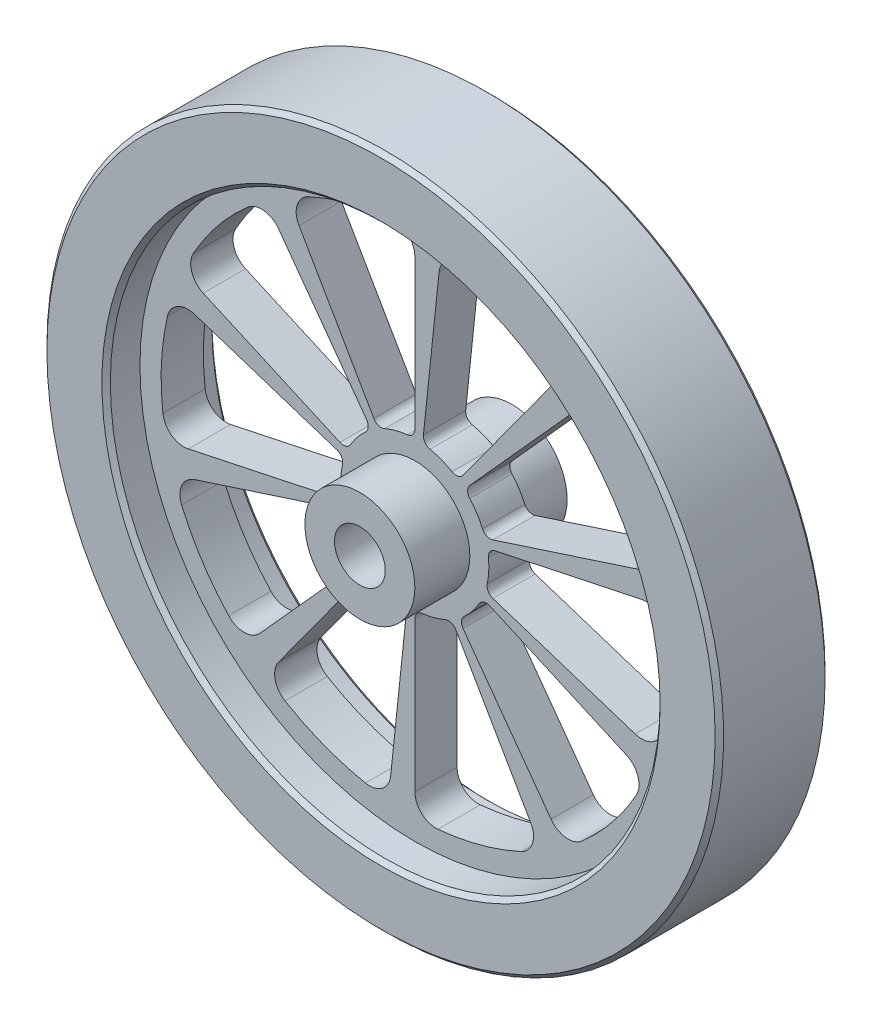
SolidWorks part; units mm, degrees
ref_plane "Front Plane" through (0, 0, 0) normal (0, 0, 1) x (1, 0, 0)
ref_plane "Top Plane" through (0, 0, 0) normal (0, 1, 0) x (1, 0, 0)
ref_plane "Right Plane" through (0, 0, 0) normal (1, 0, 0) x (0, 0, -1)
sketch "Sketch1" plane through (0, 0, 0) normal (0, 0, 1) x (1, 0, 0)
  circle A0 centre (0, 0) radius 80
  circle A1 centre (0, 0) radius 6
  dimension "D1" = 160
  dimension "D2" = 12
extrude "Boss-Extrude1" add sketch "Sketch1" along normal mid plane 26
sketch "Sketch2" plane through (0, 0, 13) normal (0, 0, 1) x (1, 0, 0)
  circle A0 centre (0, 0) radius 65
  dimension "D1" = 130
extrude "Cut-Extrude1" cut sketch "Sketch2" against normal blind 8
mirror "Mirror1" about plane through (0, 0, 0) normal (0, 0, 1) of "Cut-Extrude1"
sketch "Sketch3" plane through (0, 0, 0) normal (0, 0, 1) x (1, 0, 0)
  circle A0 centre (0, 0) radius 6 construction
  circle A1 centre (0, 0) radius 6
  circle A2 centre (0, 0) radius 13
  dimension "D1" = 26
extrude "Boss-Extrude2" add sketch "Sketch3" along normal mid plane 36
chamfer "Chamfer1" distance 1 angle 45 2 edges at (80, 0, -13) (80, 0, 13)
sketch "Sketch4" plane through (0, 0, 5) normal (0, 0, 1) x (1, 0, 0)
  line L0 (0, 17.5) -> (0, 60) construction
  line L1 (0, 0) -> (-30, 51.9615) construction
  line L2 (0, 54.7723) -> (0, 19.3972)
  line L3 (-9.6986, 16.7984) -> (-27.3861, 47.4342)
  arc A0 (-1.7949, 17.4077) -> (-7.1495, 15.973) centre (0, 0) ccw
  arc A1 (-5.4545, 59.7516) -> (-25.152, 54.4736) centre (0, 0) ccw
  arc A2 (-1.7949, 17.4077) -> (0, 19.3972) centre (-2, 19.3972) ccw
  arc A3 (-7.1495, 15.973) -> (-9.6986, 16.7984) centre (-7.9665, 17.7984) cw
  arc A4 (0, 54.7723) -> (-5.4545, 59.7516) centre (-5, 54.7723) ccw
  arc A5 (-25.152, 54.4736) -> (-27.3861, 47.4342) centre (-23.056, 49.9342) ccw
  point P11 (-8.75, 15.1554)
  dimension "D1" = 120
  dimension "D2" = 35
  dimension "D4" = 2
  dimension "D5" = 5
  dimension "D3" = 30
extrude "Cut-Extrude2" cut sketch "Sketch4" against normal through all
pattern_circular "CirPattern2" count 10 over 360 about axis through (0, 0, 0) along (0, 0, 1) of "Cut-Extrude2"
